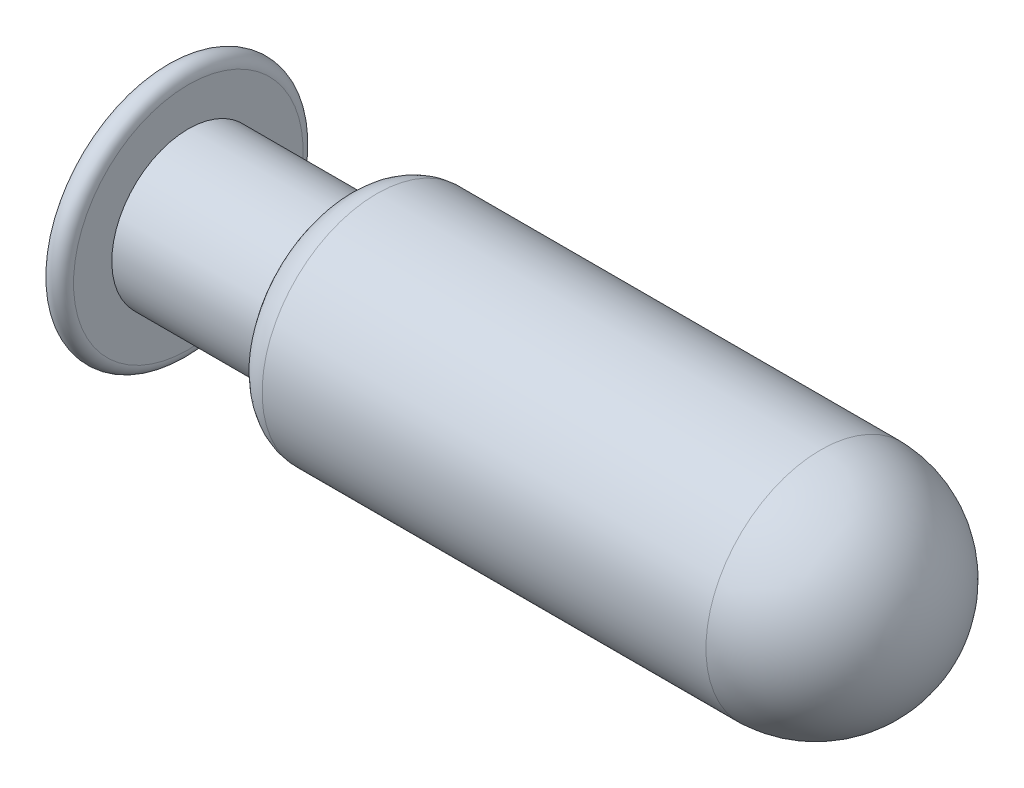
SolidWorks part; units mm, degrees
ref_plane "Front Plane" through (0, 0, 0) normal (0, 0, 1) x (1, 0, 0)
ref_plane "Top Plane" through (0, 0, 0) normal (0, 1, 0) x (1, 0, 0)
ref_plane "Right Plane" through (0, 0, 0) normal (1, 0, 0) x (0, 0, -1)
sketch "Sketch1" plane through (0, 0, 0) normal (0, 0, 1) x (1, 0, 0)
  line L0 (0, 0) -> (0, 15)
  line L2 (3, 15) -> (3, 10)
  line L5 (100, 0) -> (0, 0)
  line L8 (0, 15) -> (3, 15) construction
  line L10 (3, 10) -> (23, 10)
  line L15 (27.6343, 14.9866) -> (85.6337, 14.9866)
  arc A5 (3, 15) -> (0, 15) centre (1.5, 15) ccw
  arc A7 (100, 0) -> (85.6337, 14.9866) centre (85, 0) ccw
  arc A11 (23, 10) -> (27.6343, 14.9866) centre (28, 10) cw
  dimension "D1" = 15
  dimension "D4" = 10
  dimension "D6" = 77
  dimension "D3" = 100
  dimension "D2" = 30
  dimension "D5" = 3
  dimension "D8" = 5
  dimension "D7" = 57.9993
revolve "Revolve1" add sketch "Sketch1" angle 360 about L5
